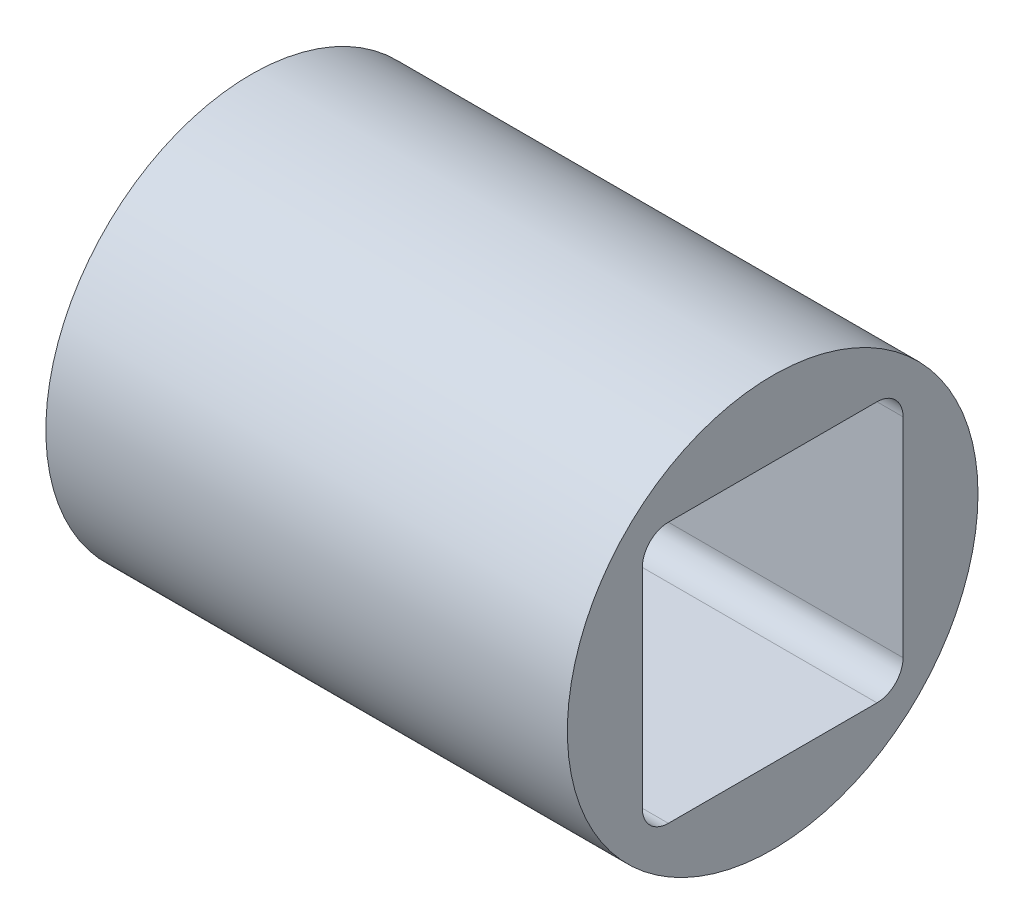
SolidWorks part; units mm, degrees
ref_plane "Front" through (0, 0, 0) normal (0, 0, 1) x (1, 0, 0)
ref_plane "Top" through (0, 0, 0) normal (0, 1, 0) x (1, 0, 0)
ref_plane "Right" through (0, 0, 0) normal (1, 0, 0) x (0, 0, -1)
sketch "Sketch1" plane through (0, 0, 0) normal (1, 0, 0) x (0, 0, -1)
  line L1 (3.175, -3.175) -> (-3.175, -3.175)
  line L2 (3.175, -3.175) -> (3.175, 3.175)
  line L3 (3.175, 3.175) -> (-3.175, 3.175)
  line L4 (-3.175, -3.175) -> (-3.175, 3.175)
  line L5 (3.175, -3.175) -> (-3.175, 3.175) construction
  line L6 (3.175, 3.175) -> (-3.175, -3.175) construction
  circle A0 centre (0, 0) radius 5
  dimension "D1" = 10
  dimension "D2" = 6.35
extrude "Boss-Extrude1" add sketch "Sketch1" along normal blind 12.7
fillet "Fillet1" radius 0.635 4 edges at (6.35, 3.175, -3.175) (6.35, 3.175, 3.175) (6.35, -3.175, 3.175) (6.35, -3.175, -3.175)
